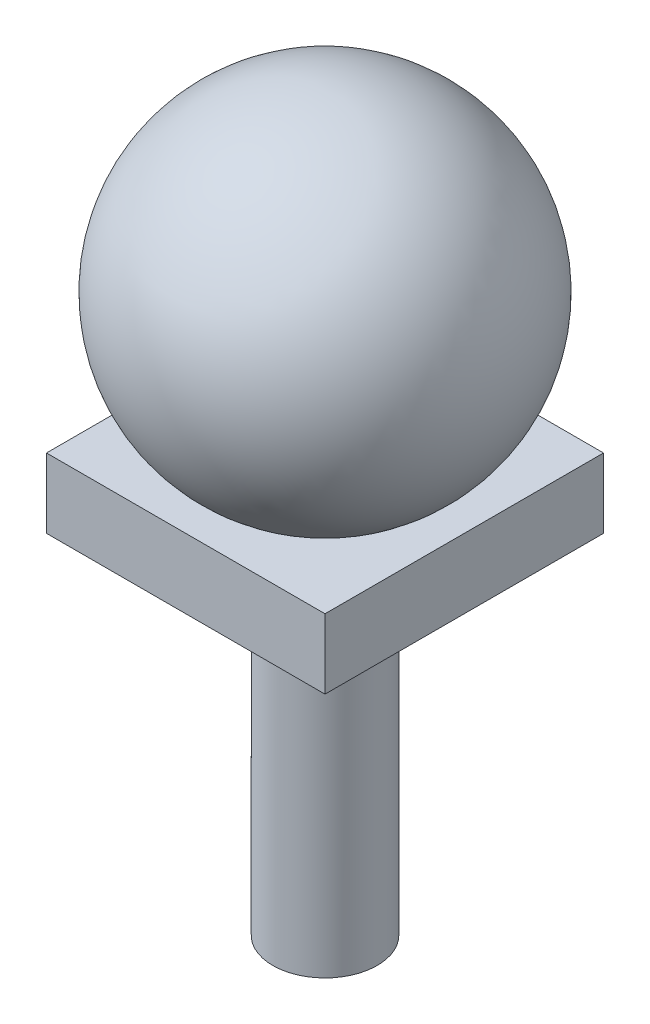
SolidWorks part; units mm, degrees
material "Chrome Stainless Steel"
ref_plane "Front Plane" through (0, 0, 0) normal (0, 0, 1) x (1, 0, 0)
ref_plane "Top Plane" through (0, 0, 0) normal (0, 1, 0) x (1, 0, 0)
ref_plane "Right Plane" through (0, 0, 0) normal (1, 0, 0) x (0, 0, -1)
sketch "Sketch1" plane through (0, 0, 0) normal (0, 0, 1) x (1, 0, 0)
  line L0 (0, 5) -> (0, -5)
  line L1 (-1.5, -5) -> (-1.5, -4.7697)
  line L2 (0, -5) -> (-1.5, -5) construction
  line L3 (0, -5) -> (0, -16)
  line L4 (0, -16) -> (-1.5, -16)
  line L5 (-1.5, -5) -> (-1.5, -16)
  arc A0 (-1.5, -4.7697) -> (0, 5) centre (0, 0) cw
  point P7 (0, 0)
  dimension "D1" = 5
  dimension "D2" = 1.5
  dimension "D3" = 11
  dimension "D4" = 5
revolve "Revolve1" add sketch "Sketch1" angle 360 about L0
ref_plane "Plane1" through (0, -6, 0) normal (0, -1, 0) x (-1, 0, 0)
sketch "Sketch2" plane through (0, -6, 0) normal (0, -1, 0) x (-1, 0, 0)
  line L1 (4, -4) -> (-4, -4)
  line L2 (4, -4) -> (4, 4)
  line L3 (4, 4) -> (-4, 4)
  line L4 (-4, -4) -> (-4, 4)
  line L5 (4, -4) -> (-4, 4) construction
  line L6 (4, 4) -> (-4, -4) construction
  point P0 (0, 0)
  dimension "D1" = 8
  dimension "D2" = 8
extrude "Boss-Extrude1" add sketch "Sketch2" against normal blind 2
